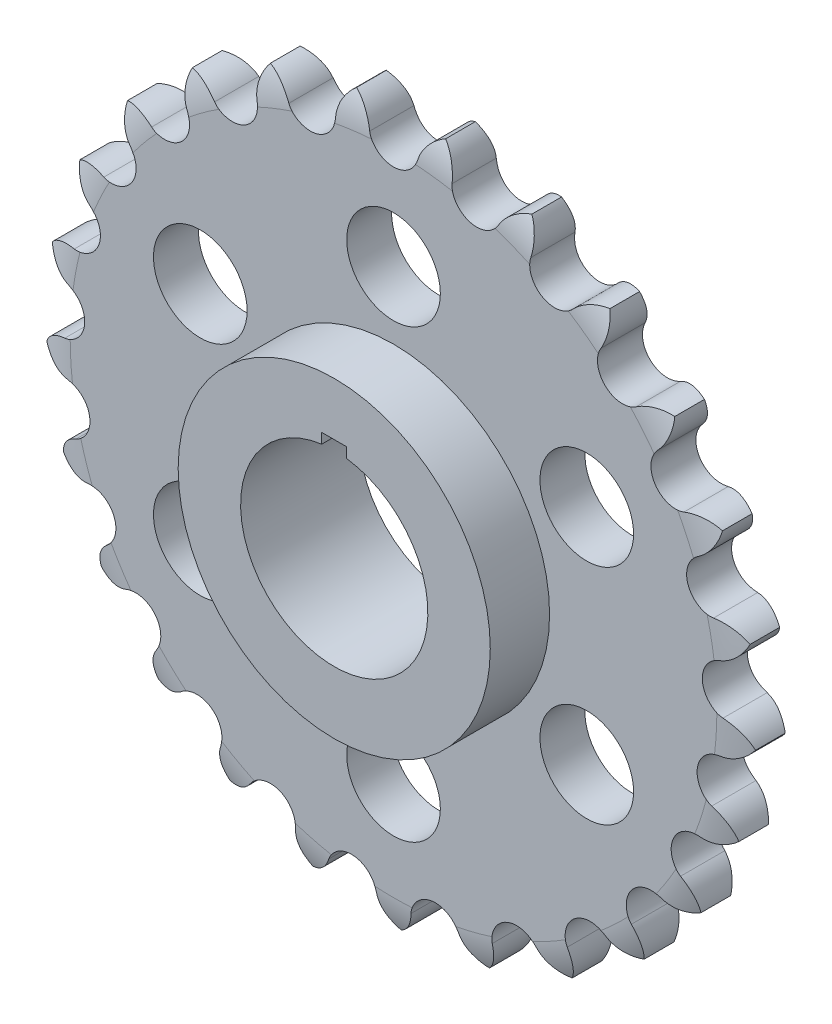
SolidWorks part; units mm, degrees
material "Acero aleado fundido"
ref_plane "Alzado" through (0, 0, 0) normal (0, 0, 1) x (1, 0, 0)
ref_plane "Planta" through (0, 0, 0) normal (0, 1, 0) x (1, 0, 0)
ref_plane "Vista lateral" through (0, 0, 0) normal (1, 0, 0) x (0, 0, -1)
sketch "Croquis1" plane through (0, 0, 0) normal (0, 0, 1) x (1, 0, 0)
  line L0 (0, 0) -> (0, 57) construction
  circle A0 centre (0, 0) radius 52 construction
  circle A1 centre (0, 0) radius 53.5 construction
  circle A2 centre (0, 0) radius 57 construction
  arc A3 (-3.8734, 52.5768) -> (3.8734, 52.5768) centre (0, 53.5753) ccw
  arc A4 (7.3334, 56.5263) -> (3.8734, 52.5768) centre (9.5188, 51.1214) ccw
  arc A5 (-7.3334, 56.5263) -> (-3.8734, 52.5768) centre (-9.5188, 51.1214) cw
  arc A6 (6.9545, 56.5742) -> (9.3236, 51.8882) centre (3.4936, 51.8825) cw
  arc A7 (9.3236, 51.8882) -> (16.827, 49.9617) centre (13.3236, 51.8922) ccw
  arc A8 (21.1606, 52.9267) -> (16.827, 49.9617) centre (21.9331, 47.1481) ccw
  arc A9 (20.8054, 53.0673) -> (21.9348, 47.9394) centre (16.2865, 49.3837) cw
  arc A10 (21.9348, 47.9394) -> (28.7233, 44.2074) centre (25.8101, 46.9484) ccw
  arc A11 (33.6581, 46.0014) -> (28.7233, 44.2074) centre (32.9693, 40.2123) ccw
  arc A12 (33.3491, 46.226) -> (33.1677, 40.9783) centre (28.0561, 43.7819) cw
  arc A13 (33.1677, 40.9783) -> (38.8148, 35.6753) centre (36.6748, 39.0547) ccw
  arc A14 (44.0408, 36.1858) -> (38.8148, 35.6753) centre (41.9339, 30.7498) ccw
  arc A15 (43.7973, 36.4801) -> (42.3166, 31.4424) centre (38.0628, 35.4292) cw
  arc A16 (42.3166, 31.4424) -> (46.4675, 24.9017) centre (45.2351, 28.7071) ccw
  arc A17 (51.6562, 24.0965) -> (46.4675, 24.9017) centre (48.2636, 19.3552) ccw
  arc A18 (51.4935, 24.4421) -> (48.8065, 19.9309) centre (45.6778, 24.8503) cw
  arc A19 (48.8065, 19.9309) -> (51.2004, 12.5633) centre (50.9532, 16.5557) ccw
  arc A20 (56.0258, 10.4931) -> (51.2004, 12.5633) centre (51.5608, 6.7445) ccw
  arc A21 (55.9543, 10.8683) -> (52.2298, 7.167) centre (50.4228, 12.7099) cw
  arc A22 (52.2298, 7.167) -> (52.7162, -0.5644) centre (53.4696, 3.364) ccw
  arc A23 (56.8752, -3.7697) -> (52.7162, -0.5644) centre (51.6182, -6.29) ccw
  arc A24 (56.8992, -3.3884) -> (52.3713, -6.0472) centre (51.9995, -0.229) cw
  arc A25 (52.3713, -6.0472) -> (50.9197, -13.6566) centre (52.6264, -10.039) ccw
  arc A26 (54.1509, -17.7955) -> (50.9197, -13.6566) centre (48.4322, -18.9294) ccw
  arc A27 (54.2689, -17.4322) -> (49.2221, -18.8814) centre (50.3089, -13.1536) cw
  arc A28 (49.2221, -18.8814) -> (45.9237, -25.8908) centre (48.4764, -22.8113) ccw
  arc A29 (48.0241, -30.7032) -> (45.9237, -25.8908) centre (42.2031, -30.3793) ccw
  arc A30 (48.2288, -30.3807) -> (42.9801, -30.5292) centre (45.4572, -25.2516) cw
  arc A31 (42.9801, -30.5292) -> (38.0421, -36.4982) centre (41.2805, -34.1502) ccw
  arc A32 (38.8797, -41.6817) -> (38.0421, -36.4982) centre (33.3222, -39.9203) ccw
  arc A33 (39.1582, -41.4202) -> (34.0375, -40.2588) centre (37.7492, -35.7631) cw
  arc A34 (34.0375, -40.2588) -> (27.7702, -44.8122) centre (31.4908, -43.3433) ccw
  arc A35 (27.2924, -50.0412) -> (27.7702, -44.8122) centre (22.3475, -46.953) ccw
  arc A36 (27.6272, -49.8572) -> (22.9561, -47.4588) centre (27.6694, -44.0273) cw
  arc A37 (22.9561, -47.4588) -> (15.7534, -50.3105) centre (19.7224, -49.8131) ccw
  arc A38 (13.9903, -55.2564) -> (15.7534, -50.3105) centre (9.9687, -51.0355) ccw
  arc A39 (14.3602, -55.1614) -> (10.4324, -51.6767) centre (15.8509, -49.5252) cw
  arc A40 (10.4324, -51.6767) -> (2.7468, -52.6476) centre (6.7148, -53.1529) ccw
  arc A41 (-0.191, -56.9997) -> (2.7468, -52.6476) centre (-3.0365, -51.9113) ccw
  arc A42 (0.191, -56.9997) -> (-2.7468, -52.6476) centre (3.0365, -51.9113) cw
  arc A43 (-2.7468, -52.6476) -> (-10.4324, -51.6767) centre (-6.7148, -53.1529) ccw
  arc A44 (-14.3602, -55.1614) -> (-10.4324, -51.6767) centre (-15.8509, -49.5252) ccw
  arc A45 (-13.9903, -55.2564) -> (-15.7534, -50.3105) centre (-9.9687, -51.0355) cw
  arc A46 (-15.7534, -50.3105) -> (-22.9561, -47.4588) centre (-19.7224, -49.8131) ccw
  arc A47 (-27.6272, -49.8572) -> (-22.9561, -47.4588) centre (-27.6694, -44.0273) ccw
  arc A48 (-27.2924, -50.0412) -> (-27.7702, -44.8122) centre (-22.3475, -46.953) cw
  arc A49 (-27.7702, -44.8122) -> (-34.0375, -40.2588) centre (-31.4908, -43.3433) ccw
  arc A50 (-39.1582, -41.4202) -> (-34.0375, -40.2588) centre (-37.7492, -35.7631) ccw
  arc A51 (-38.8797, -41.6817) -> (-38.0421, -36.4982) centre (-33.3222, -39.9203) cw
  arc A52 (-38.0421, -36.4982) -> (-42.9801, -30.5292) centre (-41.2805, -34.1502) ccw
  arc A53 (-48.2288, -30.3807) -> (-42.9801, -30.5292) centre (-45.4572, -25.2516) ccw
  arc A54 (-48.0241, -30.7032) -> (-45.9237, -25.8908) centre (-42.2031, -30.3793) cw
  arc A55 (-45.9237, -25.8908) -> (-49.2221, -18.8814) centre (-48.4764, -22.8113) ccw
  arc A56 (-54.2689, -17.4322) -> (-49.2221, -18.8814) centre (-50.3089, -13.1536) ccw
  arc A57 (-54.1509, -17.7955) -> (-50.9197, -13.6566) centre (-48.4322, -18.9294) cw
  arc A58 (-50.9197, -13.6566) -> (-52.3713, -6.0472) centre (-52.6264, -10.039) ccw
  arc A59 (-56.8992, -3.3884) -> (-52.3713, -6.0472) centre (-51.9995, -0.229) ccw
  arc A60 (-56.8752, -3.7697) -> (-52.7162, -0.5644) centre (-51.6182, -6.29) cw
  arc A61 (-52.7162, -0.5644) -> (-52.2298, 7.167) centre (-53.4696, 3.364) ccw
  arc A62 (-55.9543, 10.8683) -> (-52.2298, 7.167) centre (-50.4228, 12.7099) ccw
  arc A63 (-56.0258, 10.4931) -> (-51.2004, 12.5633) centre (-51.5608, 6.7445) cw
  arc A64 (-51.2004, 12.5633) -> (-48.8065, 19.9309) centre (-50.9532, 16.5557) ccw
  arc A65 (-51.4935, 24.4421) -> (-48.8065, 19.9309) centre (-45.6778, 24.8503) ccw
  arc A66 (-51.6562, 24.0965) -> (-46.4675, 24.9017) centre (-48.2636, 19.3552) cw
  arc A67 (-46.4675, 24.9017) -> (-42.3166, 31.4424) centre (-45.2351, 28.7071) ccw
  arc A68 (-43.7973, 36.4801) -> (-42.3166, 31.4424) centre (-38.0628, 35.4292) ccw
  arc A69 (-44.0408, 36.1858) -> (-38.8148, 35.6753) centre (-41.9339, 30.7498) cw
  arc A70 (-38.8148, 35.6753) -> (-33.1677, 40.9783) centre (-36.6748, 39.0547) ccw
  arc A71 (-33.3491, 46.226) -> (-33.1677, 40.9783) centre (-28.0561, 43.7819) ccw
  arc A72 (-33.6581, 46.0014) -> (-28.7233, 44.2074) centre (-32.9693, 40.2123) cw
  arc A73 (-28.7233, 44.2074) -> (-21.9348, 47.9394) centre (-25.8101, 46.9484) ccw
  arc A74 (-20.8054, 53.0673) -> (-21.9348, 47.9394) centre (-16.2865, 49.3837) ccw
  arc A75 (-21.1606, 52.9267) -> (-16.827, 49.9617) centre (-21.9331, 47.1481) cw
  arc A76 (-16.827, 49.9617) -> (-9.3236, 51.8882) centre (-13.3236, 51.8922) ccw
  arc A77 (-6.9545, 56.5742) -> (-9.3236, 51.8882) centre (-3.4936, 51.8825) ccw
  circle A78 centre (0, 0) radius 15
  point P184 (0, 0)
  dimension "D1" = 114
  dimension "D2" = 107
  dimension "D3" = 104
  dimension "D4" = 8
  dimension "D5" = 11.66
  dimension "D6" = 25
  dimension "D7" = 30
extrude "Saliente-Extruir1" add sketch "Croquis1" along normal mid plane 7.2 contours A5 A77 A76 A75 A74 A73 A72 A71 A70 A69 A68 A67 A66 A65 A64 A63 A62 A61 A60 A59 A58 A57 A56 A55 A54 A53 A52 A51 A50 A49 A48 A47 A46 A45 A44 A43 A42 A41 A40 A39 A38 A37 A36 A35 A34 A33 A32 A31 A30 A29 A28
sketch "Croquis2" plane through (0, 0, 3.6) normal (0, 0, 1) x (1, 0, 0)
  line L0 (0, 0) -> (0, 49.5753) construction
  arc A0 (-3.8734, 52.5768) -> (3.8734, 52.5768) centre (0, 53.5753) ccw construction
  circle A1 centre (0, 35.7427) radius 7.5
  circle A2 centre (30.9541, 17.8714) radius 7.5
  circle A3 centre (30.9541, -17.8714) radius 7.5
  circle A4 centre (0, -35.7427) radius 7.5
  circle A5 centre (-30.9541, -17.8714) radius 7.5
  circle A6 centre (-30.9541, 17.8714) radius 7.5
  point P20 (0, 0)
  dimension "D1" = 15
  dimension "D2" = 6
extrude "Cortar-Extruir1" cut sketch "Croquis2" against normal up to surface (7.2 mm away) up to face at (15, 0, -3.6)
sketch "Croquis3" plane through (0, 0, 3.6) normal (0, 0, 1) x (1, 0, 0)
  circle A0 centre (0, 0) radius 25
  circle A1 centre (0, 0) radius 7.5045
  dimension "D1" = 50
extrude "Saliente-Extruir2" add sketch "Croquis3" along normal mid plane 19
sketch "Croquis4" plane through (0, 0, 13.1) normal (0, 0, 1) x (1, 0, 0)
  line L0 (0, 0) -> (0, 7.5045) construction
  line L2 (-2, 6.0045) -> (2, 6.0045)
  line L3 (-2, 6.0045) -> (-2, 9.0045)
  line L4 (-2, 9.0045) -> (2, 9.0045)
  line L5 (2, 6.0045) -> (2, 9.0045)
  line L6 (-2, 6.0045) -> (2, 9.0045) construction
  line L7 (-2, 9.0045) -> (2, 6.0045) construction
  circle A0 centre (0, 0) radius 7.5045 construction
  dimension "D1" = 4
  dimension "D2" = 3
extrude "Cortar-Extruir2" cut sketch "Croquis4" against normal through all
sketch "Croquis5" plane through (0, 0, 0) normal (1, 0, 0) x (0, 0, -1)
  line L0 (0, 0) -> (0, 65.0777) construction
  line L1 (-2.1, 65.0777) -> (-2.1, 31.8811) construction
  line L2 (-3.6, 56.4395) -> (-3.6, 51.8882) construction
  line L3 (-2.1, 57.4395) -> (-9.7849, 57.4395)
  line L4 (-9.7849, 57.4395) -> (-9.7849, 51.0895)
  line L5 (-9.7849, 51.0895) -> (-3.6, 51.0895)
  line L6 (-3.6, 56.4395) -> (3.6, 56.4395) construction
  line L7 (-3.6, 52.8932) -> (-3.6, 47.9394) construction
  line L8 (9.7849, 51.0895) -> (3.6, 51.0895)
  line L9 (9.7849, 57.4395) -> (9.7849, 51.0895)
  line L10 (2.1, 57.4395) -> (9.7849, 57.4395)
  arc A0 (-2.1, 57.4395) -> (-3.6, 51.0895) centre (9.0951, 51.4428) ccw
  arc A1 (2.1, 57.4395) -> (3.6, 51.0895) centre (-9.0951, 51.4428) cw
  dimension "D2" = 12.7
  dimension "D1" = 1.5
  dimension "D3" = 1
  dimension "D4" = 6.35
ref_axis "Eje1" through (0, 0, 13.1) along (0, 0, -1)
revolve "Cortar-Revolución1" cut sketch "Croquis5" angle 360 about axis through (0, 0, 13.1) along (0, 0, -1)
sketch "Croquis6" plane through (0, 0, -5.9) normal (0, 0, -1) x (-1, 0, 0)
  circle A0 centre (0, 0) radius 15
  dimension "D1" = 30
extrude "Cortar-Extruir3" cut sketch "Croquis6" against normal through all
sketch "Croquis7" plane through (0, 0, 13.1) normal (0, 0, 1) x (1, 0, 0)
  line L0 (0, 0) -> (0, 15) construction
  line L2 (-2, 13.5) -> (2, 13.5)
  line L3 (-2, 13.5) -> (-2, 16.5)
  line L4 (-2, 16.5) -> (2, 16.5)
  line L5 (2, 13.5) -> (2, 16.5)
  line L6 (-2, 13.5) -> (2, 16.5) construction
  line L7 (-2, 16.5) -> (2, 13.5) construction
  circle A0 centre (0, 0) radius 15 construction
  dimension "D1" = 4
  dimension "D2" = 3
extrude "Cortar-Extruir4" cut sketch "Croquis7" against normal through all
